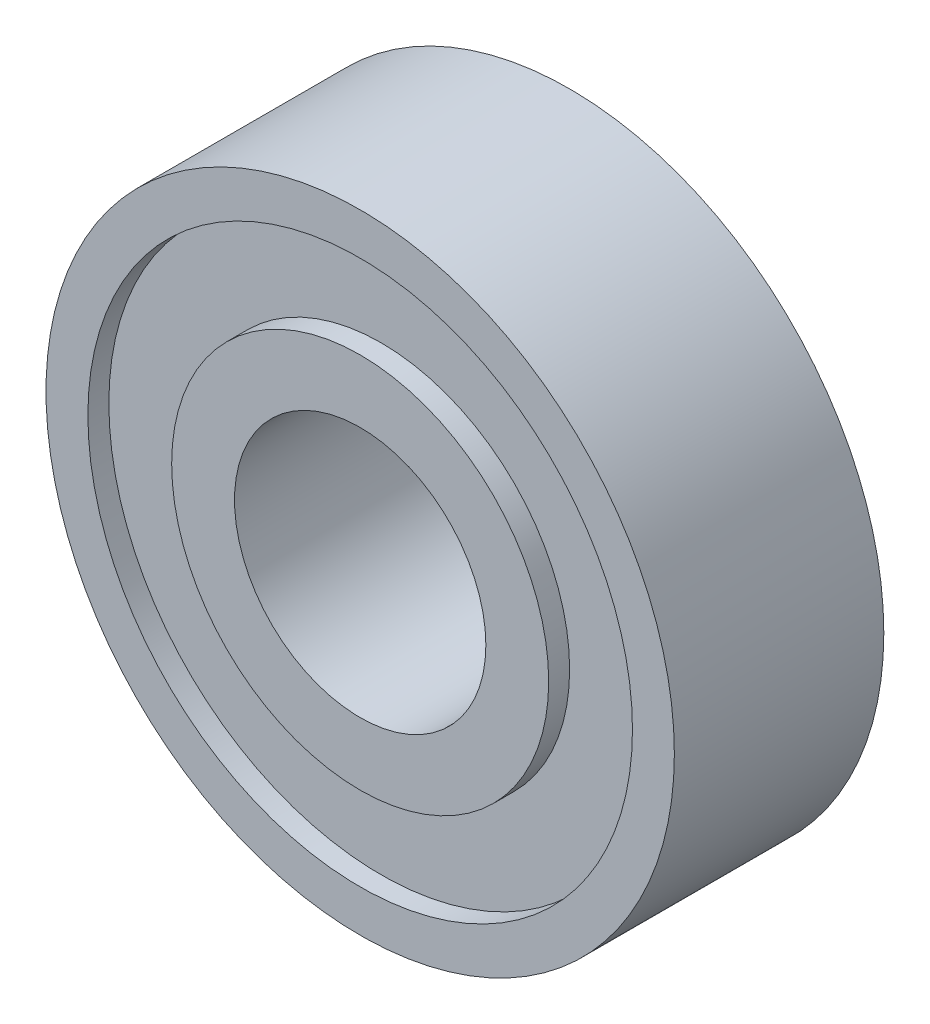
SolidWorks part; units mm, degrees
ref_plane "정면" through (0, 0, 0) normal (0, 0, 1) x (1, 0, 0)
ref_plane "윗면" through (0, 0, 0) normal (0, 1, 0) x (1, 0, 0)
ref_plane "우측면" through (0, 0, 0) normal (1, 0, 0) x (0, 0, -1)
sketch "스케치1" plane through (0, 0, 0) normal (0, 0, 1) x (1, 0, 0)
  circle A0 centre (0, 0) radius 7.5
  circle A1 centre (0, 0) radius 3
  dimension "D1" = 15
  dimension "D2" = 6
extrude "보스-돌출1" add sketch "스케치1" along normal blind 5
sketch "스케치2" plane through (0, 0, 5) normal (0, 0, 1) x (1, 0, 0)
  circle A0 centre (0, 0) radius 4.5
  circle A1 centre (0, 0) radius 3 construction
  circle A2 centre (0, 0) radius 6.5
  dimension "D1" = 1.5
  dimension "D2" = 2
extrude "컷-돌출1" cut sketch "스케치2" against normal blind 0.5
sketch "스케치3" plane through (0, 0, 0) normal (0, 0, -1) x (-1, 0, 0)
  circle A0 centre (0, 0) radius 4.5
  circle A1 centre (0, 0) radius 6.5
  circle A2 centre (0, 0) radius 3 construction
  dimension "D1" = 2
  dimension "D2" = 1.5
extrude "컷-돌출2" cut sketch "스케치3" against normal blind 0.5
